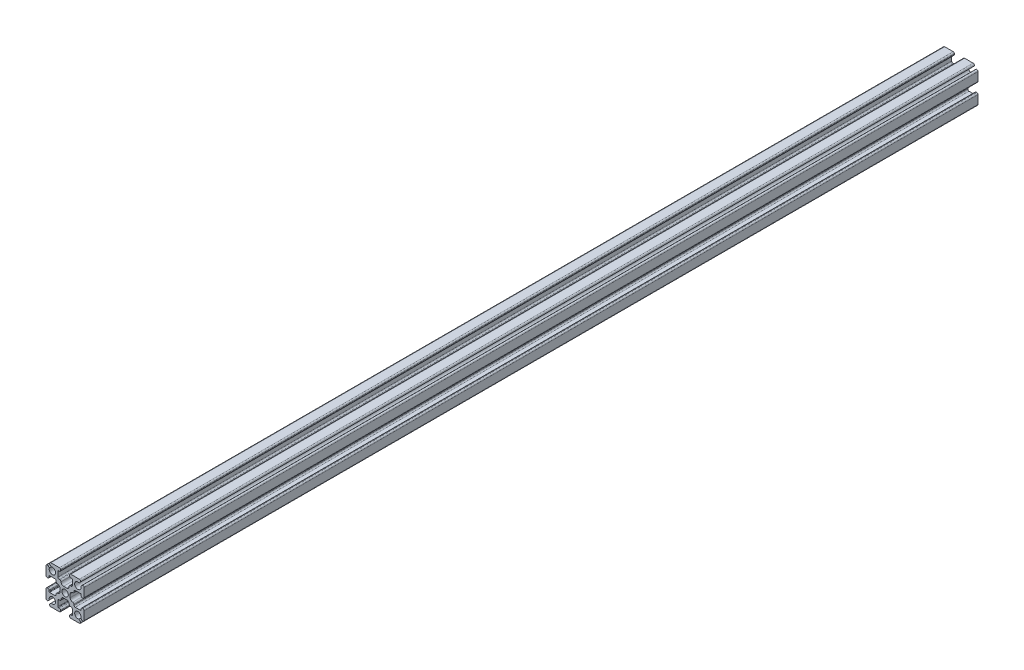
SolidWorks part; units mm, degrees
ref_plane "Front" through (0, 0, 0) normal (0, 0, 1) x (1, 0, 0)
ref_plane "Top" through (0, 0, 0) normal (0, 1, 0) x (1, 0, 0)
ref_plane "Right" through (0, 0, 0) normal (1, 0, 0) x (0, 0, -1)
sketch "Sketch1" plane through (0, 0, 0) normal (0, 0, 1) x (1, 0, 0)
  line L0 (6.6464, 5.9393) -> (6.1636, 5.4565)
  line L1 (5.4565, 6.1636) -> (5.9393, 6.6464)
  line L2 (5.5858, 7.5) -> (2.25, 7.5)
  line L3 (1.75, 7) -> (1.75, 6.8)
  line L4 (2.25, 6.3) -> (2.65, 6.3)
  line L5 (2.85, 6.1) -> (2.85, 4)
  line L6 (2.35, 3.5) -> (2.1, 3.5)
  line L7 (0.6, 2) -> (-0.6, 2)
  line L8 (-2.1, 3.5) -> (-2.35, 3.5)
  line L9 (-2.85, 4) -> (-2.85, 6.1)
  line L10 (-2.65, 6.3) -> (-2.25, 6.3)
  line L11 (-1.75, 6.8) -> (-1.75, 7)
  line L12 (-2.25, 7.5) -> (-5.5858, 7.5)
  line L13 (-5.9393, 6.6464) -> (-5.4565, 6.1636)
  line L14 (-6.1636, 5.4565) -> (-6.6464, 5.9393)
  line L15 (-7.5, 5.5858) -> (-7.5, 2.25)
  line L16 (-7, 1.75) -> (-6.8, 1.75)
  line L17 (-6.3, 2.25) -> (-6.3, 2.65)
  line L18 (-6.1, 2.85) -> (-4, 2.85)
  line L19 (-3.5, 2.35) -> (-3.5, 2.1)
  line L20 (-2, 0.6) -> (-2, -0.6)
  line L21 (-3.5, -2.1) -> (-3.5, -2.35)
  line L22 (-4, -2.85) -> (-6.1, -2.85)
  line L23 (-6.3, -2.65) -> (-6.3, -2.25)
  line L24 (-6.8, -1.75) -> (-7, -1.75)
  line L25 (-7.5, -2.25) -> (-7.5, -5.5858)
  line L26 (-6.6464, -5.9393) -> (-6.1636, -5.4565)
  line L27 (-5.4565, -6.1636) -> (-5.9393, -6.6464)
  line L28 (-5.5858, -7.5) -> (-2.25, -7.5)
  line L29 (-1.75, -7) -> (-1.75, -6.8)
  line L30 (-2.25, -6.3) -> (-2.65, -6.3)
  line L31 (-2.85, -6.1) -> (-2.85, -4)
  line L32 (-2.35, -3.5) -> (-2.1, -3.5)
  line L33 (-0.6, -2) -> (0.6, -2)
  line L34 (2.1, -3.5) -> (2.35, -3.5)
  line L35 (2.85, -4) -> (2.85, -6.1)
  line L36 (2.65, -6.3) -> (2.25, -6.3)
  line L37 (1.75, -6.8) -> (1.75, -7)
  line L38 (2.25, -7.5) -> (5.5858, -7.5)
  line L39 (5.9393, -6.6464) -> (5.4565, -6.1636)
  line L40 (6.1636, -5.4565) -> (6.6464, -5.9393)
  line L41 (7.5, -5.5858) -> (7.5, -2.25)
  line L42 (7, -1.75) -> (6.8, -1.75)
  line L43 (6.3, -2.25) -> (6.3, -2.65)
  line L44 (6.1, -2.85) -> (4, -2.85)
  line L45 (3.5, -2.35) -> (3.5, -2.1)
  line L46 (2, -0.6) -> (2, 0.6)
  line L47 (3.5, 2.1) -> (3.5, 2.35)
  line L48 (4, 2.85) -> (6.1, 2.85)
  line L49 (6.3, 2.65) -> (6.3, 2.25)
  line L50 (6.8, 1.75) -> (7, 1.75)
  line L51 (7.5, 2.25) -> (7.5, 5.5858)
  circle A0 centre (0, 0) radius 1.25
  arc A1 (6.1636, 5.4565) -> (5.4565, 6.1636) centre (5, 5) cw
  arc A2 (5.9393, 6.6464) -> (5.5858, 7.5) centre (5.5858, 7) ccw
  arc A3 (2.25, 7.5) -> (1.75, 7) centre (2.25, 7) ccw
  arc A4 (1.75, 6.8) -> (2.25, 6.3) centre (2.25, 6.8) ccw
  arc A5 (2.65, 6.3) -> (2.85, 6.1) centre (2.65, 6.1) cw
  arc A6 (2.85, 4) -> (2.35, 3.5) centre (2.35, 4) cw
  arc A7 (2.1, 3.5) -> (1.6, 3) centre (2.1, 3) ccw
  arc A8 (1.6, 3) -> (0.6, 2) centre (0.6, 3) cw
  arc A9 (-0.6, 2) -> (-1.6, 3) centre (-0.6, 3) cw
  arc A10 (-1.6, 3) -> (-2.1, 3.5) centre (-2.1, 3) ccw
  arc A11 (-2.35, 3.5) -> (-2.85, 4) centre (-2.35, 4) cw
  arc A12 (-2.85, 6.1) -> (-2.65, 6.3) centre (-2.65, 6.1) cw
  arc A13 (-2.25, 6.3) -> (-1.75, 6.8) centre (-2.25, 6.8) ccw
  arc A14 (-1.75, 7) -> (-2.25, 7.5) centre (-2.25, 7) ccw
  arc A15 (-5.5858, 7.5) -> (-5.9393, 6.6464) centre (-5.5858, 7) ccw
  arc A16 (-5.4565, 6.1636) -> (-6.1636, 5.4565) centre (-5, 5) cw
  arc A17 (-6.6464, 5.9393) -> (-7.5, 5.5858) centre (-7, 5.5858) ccw
  arc A18 (-7.5, 2.25) -> (-7, 1.75) centre (-7, 2.25) ccw
  arc A19 (-6.8, 1.75) -> (-6.3, 2.25) centre (-6.8, 2.25) ccw
  arc A20 (-6.3, 2.65) -> (-6.1, 2.85) centre (-6.1, 2.65) cw
  arc A21 (-4, 2.85) -> (-3.5, 2.35) centre (-4, 2.35) cw
  arc A22 (-3.5, 2.1) -> (-3, 1.6) centre (-3, 2.1) ccw
  arc A23 (-3, 1.6) -> (-2, 0.6) centre (-3, 0.6) cw
  arc A24 (-2, -0.6) -> (-3, -1.6) centre (-3, -0.6) cw
  arc A25 (-3, -1.6) -> (-3.5, -2.1) centre (-3, -2.1) ccw
  arc A26 (-3.5, -2.35) -> (-4, -2.85) centre (-4, -2.35) cw
  arc A27 (-6.1, -2.85) -> (-6.3, -2.65) centre (-6.1, -2.65) cw
  arc A28 (-6.3, -2.25) -> (-6.8, -1.75) centre (-6.8, -2.25) ccw
  arc A29 (-7, -1.75) -> (-7.5, -2.25) centre (-7, -2.25) ccw
  arc A30 (-7.5, -5.5858) -> (-6.6464, -5.9393) centre (-7, -5.5858) ccw
  arc A31 (-6.1636, -5.4565) -> (-5.4565, -6.1636) centre (-5, -5) cw
  arc A32 (-5.9393, -6.6464) -> (-5.5858, -7.5) centre (-5.5858, -7) ccw
  arc A33 (-2.25, -7.5) -> (-1.75, -7) centre (-2.25, -7) ccw
  arc A34 (-1.75, -6.8) -> (-2.25, -6.3) centre (-2.25, -6.8) ccw
  arc A35 (-2.65, -6.3) -> (-2.85, -6.1) centre (-2.65, -6.1) cw
  arc A36 (-2.85, -4) -> (-2.35, -3.5) centre (-2.35, -4) cw
  arc A37 (-2.1, -3.5) -> (-1.6, -3) centre (-2.1, -3) ccw
  arc A38 (-1.6, -3) -> (-0.6, -2) centre (-0.6, -3) cw
  arc A39 (0.6, -2) -> (1.6, -3) centre (0.6, -3) cw
  arc A40 (1.6, -3) -> (2.1, -3.5) centre (2.1, -3) ccw
  arc A41 (2.35, -3.5) -> (2.85, -4) centre (2.35, -4) cw
  arc A42 (2.85, -6.1) -> (2.65, -6.3) centre (2.65, -6.1) cw
  arc A43 (2.25, -6.3) -> (1.75, -6.8) centre (2.25, -6.8) ccw
  arc A44 (1.75, -7) -> (2.25, -7.5) centre (2.25, -7) ccw
  arc A45 (5.5858, -7.5) -> (5.9393, -6.6464) centre (5.5858, -7) ccw
  arc A46 (5.4565, -6.1636) -> (6.1636, -5.4565) centre (5, -5) cw
  arc A47 (6.6464, -5.9393) -> (7.5, -5.5858) centre (7, -5.5858) ccw
  arc A48 (7.5, -2.25) -> (7, -1.75) centre (7, -2.25) ccw
  arc A49 (6.8, -1.75) -> (6.3, -2.25) centre (6.8, -2.25) ccw
  arc A50 (6.3, -2.65) -> (6.1, -2.85) centre (6.1, -2.65) cw
  arc A51 (4, -2.85) -> (3.5, -2.35) centre (4, -2.35) cw
  arc A52 (3.5, -2.1) -> (3, -1.6) centre (3, -2.1) ccw
  arc A53 (3, -1.6) -> (2, -0.6) centre (3, -0.6) cw
  arc A54 (2, 0.6) -> (3, 1.6) centre (3, 0.6) cw
  arc A55 (3, 1.6) -> (3.5, 2.1) centre (3, 2.1) ccw
  arc A56 (3.5, 2.35) -> (4, 2.85) centre (4, 2.35) cw
  arc A57 (6.1, 2.85) -> (6.3, 2.65) centre (6.1, 2.65) cw
  arc A58 (6.3, 2.25) -> (6.8, 1.75) centre (6.8, 2.25) ccw
  arc A59 (7, 1.75) -> (7.5, 2.25) centre (7, 2.25) ccw
  arc A60 (7.5, 5.5858) -> (6.6464, 5.9393) centre (7, 5.5858) ccw
extrude "Boss-Extrude1" add sketch "Sketch1" along normal blind 351
